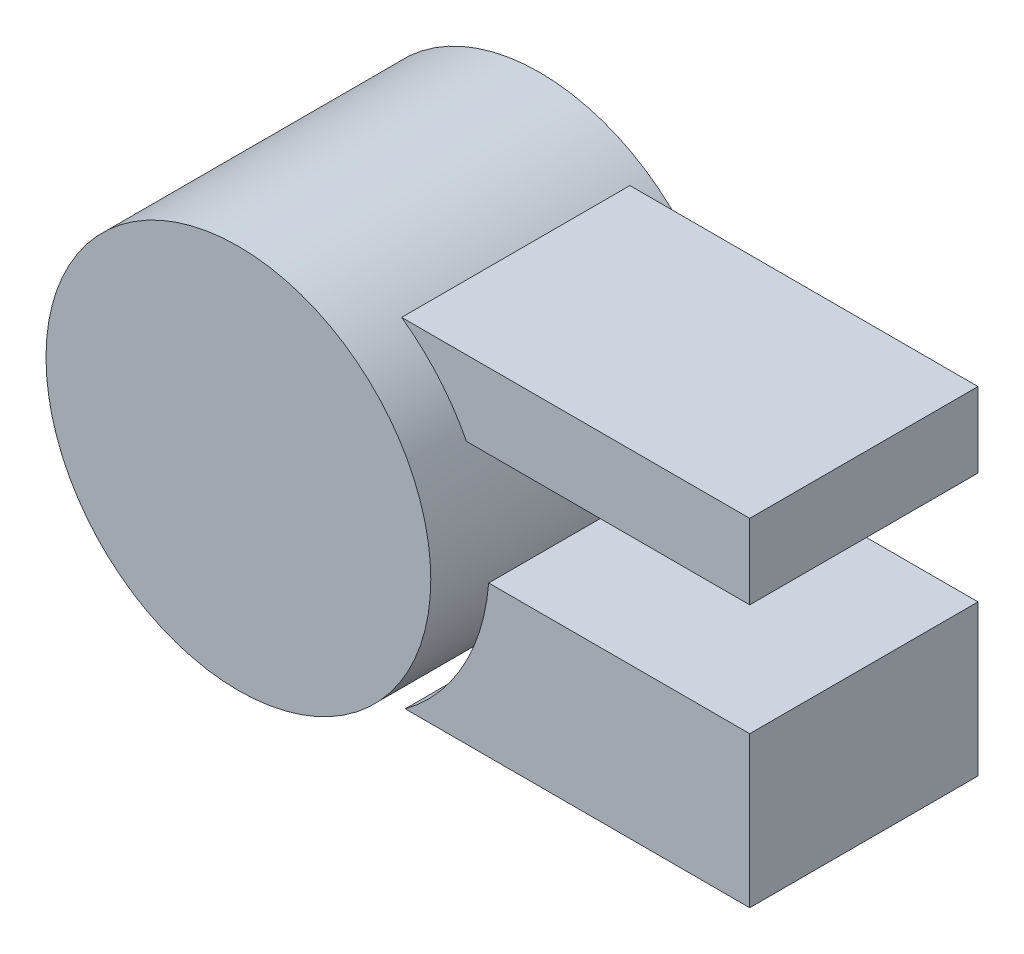
SolidWorks part; units mm, degrees
ref_plane "Front Plane" through (0, 0, 0) normal (0, 0, 1) x (1, 0, 0)
ref_plane "Top Plane" through (0, 0, 0) normal (0, 1, 0) x (1, 0, 0)
ref_plane "Right Plane" through (0, 0, 0) normal (1, 0, 0) x (0, 0, -1)
sketch "Sketch1" plane through (0, 0, 0) normal (0, 0, 1) x (1, 0, 0)
  circle A0 centre (0, 0) radius 76.0907
extrude "Boss-Extrude1" add sketch "Sketch1" along normal mid plane 119.126
ref_plane "Plane1" through (185.42, 0, 0) normal (1, 0, 0) x (0, 0, -1)
sketch "Sketch2" plane through (185.42, 0, 0) normal (1, 0, 0) x (0, 0, -1)
  line L0 (-42.7579, -6.5585) -> (47.5277, -6.5585)
  line L1 (-42.7579, 67.2032) -> (47.5277, 67.2032)
  line L2 (-42.7579, 67.2032) -> (-42.7579, -66.1811)
  line L3 (-42.7579, -66.1811) -> (47.5277, -66.1811)
  line L4 (47.5277, 67.2032) -> (47.5277, -66.1811)
  line L5 (-42.7579, 37.5622) -> (47.5277, 37.5622)
extrude "Boss-Extrude2" add sketch "Sketch2" against normal offset from surface (136.2616 mm away) 6.35 separate body contours L4 L0 L2 L3 | L2 L5 L4 L1
